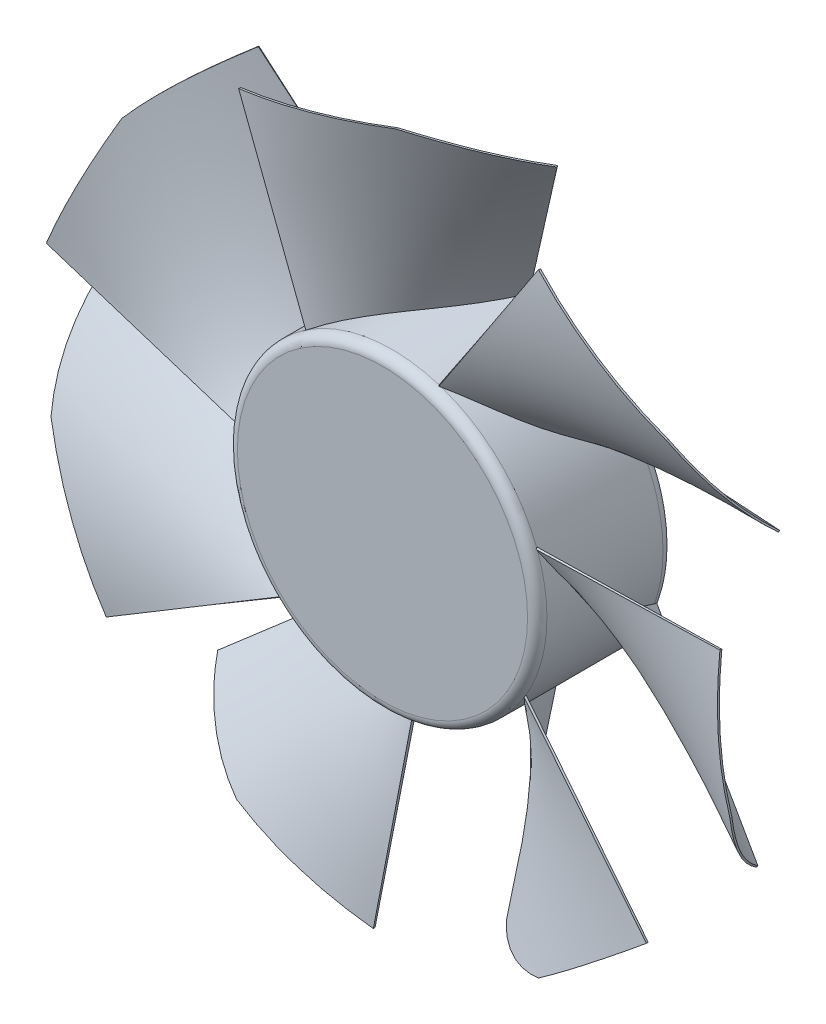
SolidWorks part; units mm, degrees
ref_plane "Спереди" through (0, 0, 0) normal (0, 0, 1) x (1, 0, 0)
ref_plane "Сверху" through (0, 0, 0) normal (0, 1, 0) x (1, 0, 0)
ref_plane "Справа" through (0, 0, 0) normal (1, 0, 0) x (0, 0, -1)
sketch "Эскиз1" plane through (0, 0, 0) normal (0, 0, 1) x (1, 0, 0)
  circle A0 centre (0, 0) radius 16
extrude "Вытянуть1" add sketch "Эскиз1" along normal blind 14
fillet "Скругление1" radius 1 2 edges at (16, 0, 0) (16, 0, 14)
ref_axis "Ось1" through (0, 0, 13) along (0, 0, -1)
ref_plane "Плоскость1" through (13, 0, 0) normal (1, 0, 0) x (0, 0, -1)
ref_plane "Плоскость3" through (35, 0, 0) normal (1, 0, 0) x (0, 0, -1)
sketch "Эскиз2" plane through (13, 0, 0) normal (1, 0, 0) x (0, 0, -1)
  line L0 (-0.065, -3.8609) -> (0, -3.6718)
  line L3 (-13, -16) -> (-13, 16) construction
  line L4 (-13, -16) -> (-13, 16) construction
  line L5 (-13, 5.4798) -> (-12.8409, 5.601)
  arc A2 (-13, 5.4798) -> (-0.065, -3.8609) centre (8.8816, 22.1548) ccw
  arc A3 (-12.8409, 5.601) -> (0, -3.6718) centre (8.8816, 22.1548) ccw
  point P2 (-13.9192, 7.1208)
  point P3 (-14.0861, 7.0107)
sketch "Эскиз3" plane through (35, 0, 0) normal (1, 0, 0) x (0, 0, -1)
  line L0 (-13.9192, 7.1208) -> (-14.118, 7.1422)
  line L1 (-7.9128, -20.9655) -> (-7.7415, -20.8624)
  arc A0 (-14.118, 7.1422) -> (-7.9128, -20.9655) centre (30.7731, 2.3137) ccw
  arc A1 (-13.9192, 7.1208) -> (-7.7415, -20.8624) centre (30.7731, 2.3137) ccw
  dimension "D1" = 0.2
loft "По сечениям1" add profiles "Эскиз3", "Эскиз2"
pattern_circular "Круговой массив1" count 7 over 360 about axis through (0, 0, 13) along (0, 0, -1) of "По сечениям1"
sketch "Эскиз4" plane through (0, 0, 0) normal (0, 0, 1) x (1, 0, 0)
  circle A0 centre (0, 0) radius 36
  dimension "D1" = 72
extrude "Вырез-Вытянуть2" cut sketch "Эскиз4" along normal blind 14 flip side to cut
